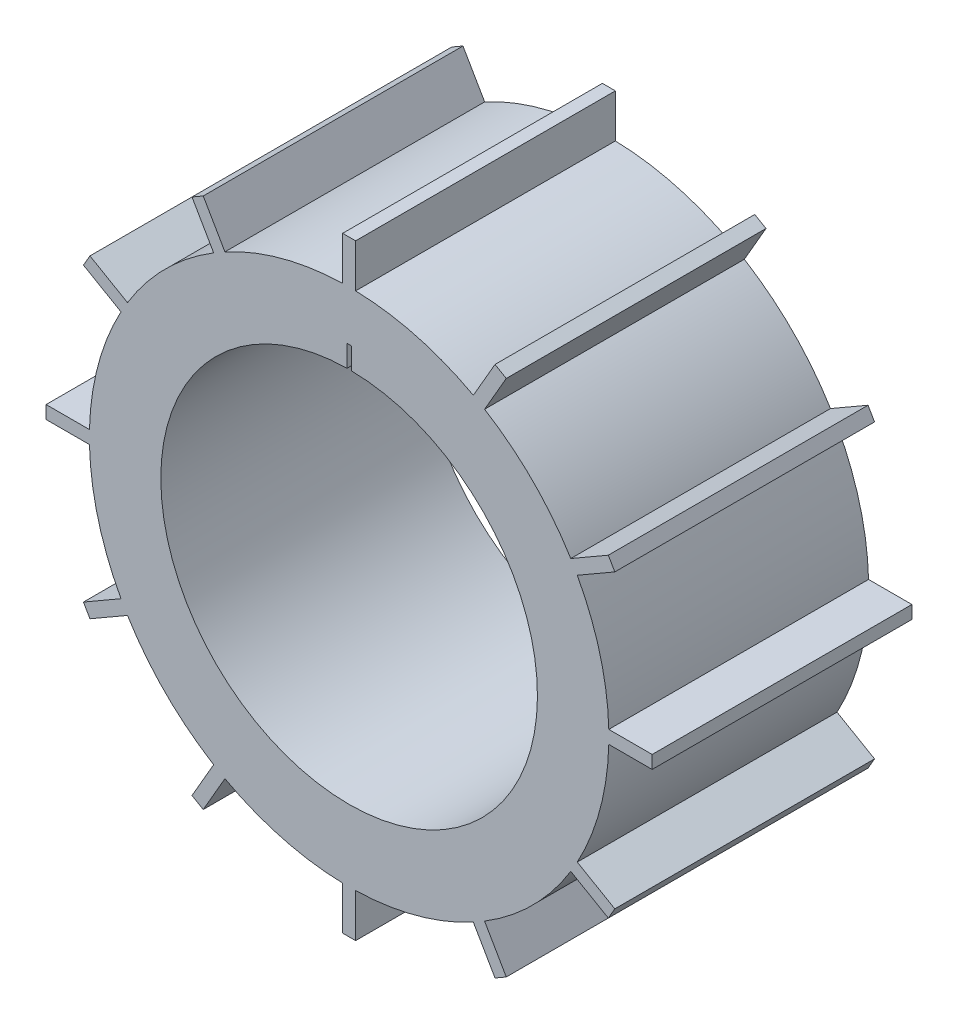
SolidWorks part; units mm, degrees
ref_plane "Front Plane" through (0, 0, 0) normal (0, 0, 1) x (1, 0, 0)
ref_plane "Top Plane" through (0, 0, 0) normal (0, 1, 0) x (1, 0, 0)
ref_plane "Right Plane" through (0, 0, 0) normal (1, 0, 0) x (0, 0, -1)
ref_plane "Plane1"
sketch "Sketch1" plane through (0, 0, 0) normal (0, 0, 1) x (1, 0, 0)
  circle A0 centre (0, 0) radius 60
  circle A1 centre (0, 0) radius 43.5
  dimension "D1" = 87
  dimension "D2" = 120
extrude "Extrusion1" add sketch "Sketch1" along normal blind 60 contours A0 A1
ref_plane "Plane2"
sketch "Sketch2" plane through (0, 0, 60) normal (0, 0, 1) x (1, 0, 0)
  line L0 (33.701, 61.3718) -> (28.6916, 52.6953)
  line L1 (-1.5, 70) -> (-1.5, 59.9812)
  line L2 (1.5, 70) -> (1.5, 59.9812)
  line L4 (-1.5, 70) -> (1.5, 70)
  line L5 (33.701, 61.3718) -> (36.299, 59.8718)
  line L6 (36.299, 59.8718) -> (31.2897, 51.1953)
  line L7 (59.8718, 36.299) -> (51.1953, 31.2897)
  line L8 (59.8718, 36.299) -> (61.3718, 33.701)
  line L9 (61.3718, 33.701) -> (52.6953, 28.6916)
  line L10 (70, 1.5) -> (59.9812, 1.5)
  line L11 (70, 1.5) -> (70, -1.5)
  line L12 (70, -1.5) -> (59.9812, -1.5)
  line L13 (61.3718, -33.701) -> (52.6953, -28.6916)
  line L14 (61.3718, -33.701) -> (59.8718, -36.299)
  line L15 (59.8718, -36.299) -> (51.1953, -31.2897)
  line L16 (36.299, -59.8718) -> (31.2897, -51.1953)
  line L17 (36.299, -59.8718) -> (33.701, -61.3718)
  line L18 (33.701, -61.3718) -> (28.6916, -52.6953)
  line L19 (1.5, -70) -> (1.5, -59.9812)
  line L20 (1.5, -70) -> (-1.5, -70)
  line L21 (-1.5, -70) -> (-1.5, -59.9812)
  line L22 (-33.701, -61.3718) -> (-28.6916, -52.6953)
  line L23 (-33.701, -61.3718) -> (-36.299, -59.8718)
  line L24 (-36.299, -59.8718) -> (-31.2897, -51.1953)
  line L25 (-59.8718, -36.299) -> (-51.1953, -31.2897)
  line L26 (-59.8718, -36.299) -> (-61.3718, -33.701)
  line L27 (-61.3718, -33.701) -> (-52.6953, -28.6916)
  line L28 (-70, -1.5) -> (-59.9812, -1.5)
  line L29 (-70, -1.5) -> (-70, 1.5)
  line L30 (-70, 1.5) -> (-59.9812, 1.5)
  line L31 (-61.3718, 33.701) -> (-52.6953, 28.6916)
  line L32 (-61.3718, 33.701) -> (-59.8718, 36.299)
  line L33 (-59.8718, 36.299) -> (-51.1953, 31.2897)
  line L34 (-36.299, 59.8718) -> (-31.2897, 51.1953)
  line L35 (-36.299, 59.8718) -> (-33.701, 61.3718)
  line L36 (-33.701, 61.3718) -> (-28.6916, 52.6953)
  arc A0 (1.5, 59.9812) -> (-1.5, 59.9812) centre (0, 0) ccw
  arc A1 (31.2897, 51.1953) -> (28.6916, 52.6953) centre (0, 0) ccw
  arc A2 (52.6953, 28.6916) -> (51.1953, 31.2897) centre (0, 0) ccw
  arc A3 (59.9812, -1.5) -> (59.9812, 1.5) centre (0, 0) ccw
  arc A4 (51.1953, -31.2897) -> (52.6953, -28.6916) centre (0, 0) ccw
  arc A5 (28.6916, -52.6953) -> (31.2897, -51.1953) centre (0, 0) ccw
  arc A6 (-1.5, -59.9812) -> (1.5, -59.9812) centre (0, 0) ccw
  arc A7 (-31.2897, -51.1953) -> (-28.6916, -52.6953) centre (0, 0) ccw
  arc A8 (-52.6953, -28.6916) -> (-51.1953, -31.2897) centre (0, 0) ccw
  arc A9 (-59.9812, 1.5) -> (-59.9812, -1.5) centre (0, 0) ccw
  arc A10 (-51.1953, 31.2897) -> (-52.6953, 28.6916) centre (0, 0) ccw
  arc A11 (-28.6916, 52.6953) -> (-31.2897, 51.1953) centre (0, 0) ccw
  point P52 (0, 0)
  dimension "D1" = 12
ref_plane "Plane3"
sketch "Sketch3" plane through (0, 0, 60) normal (0, 0, 1) x (1, 0, 0)
  line L0 (-0.5, 48.5) -> (-0.5, 43.4971)
  line L1 (0.5, 43.4971) -> (0.5, 48.5)
  line L2 (0.5, 48.5) -> (-0.5, 48.5)
  arc A0 (0.5, 43.4971) -> (-0.5, 43.4971) centre (0, 0) ccw
extrude "Extrusion3" cut sketch "Sketch3" against normal blind 60
extrude "Boss-Extrude2" add sketch "Sketch2" against normal through all
